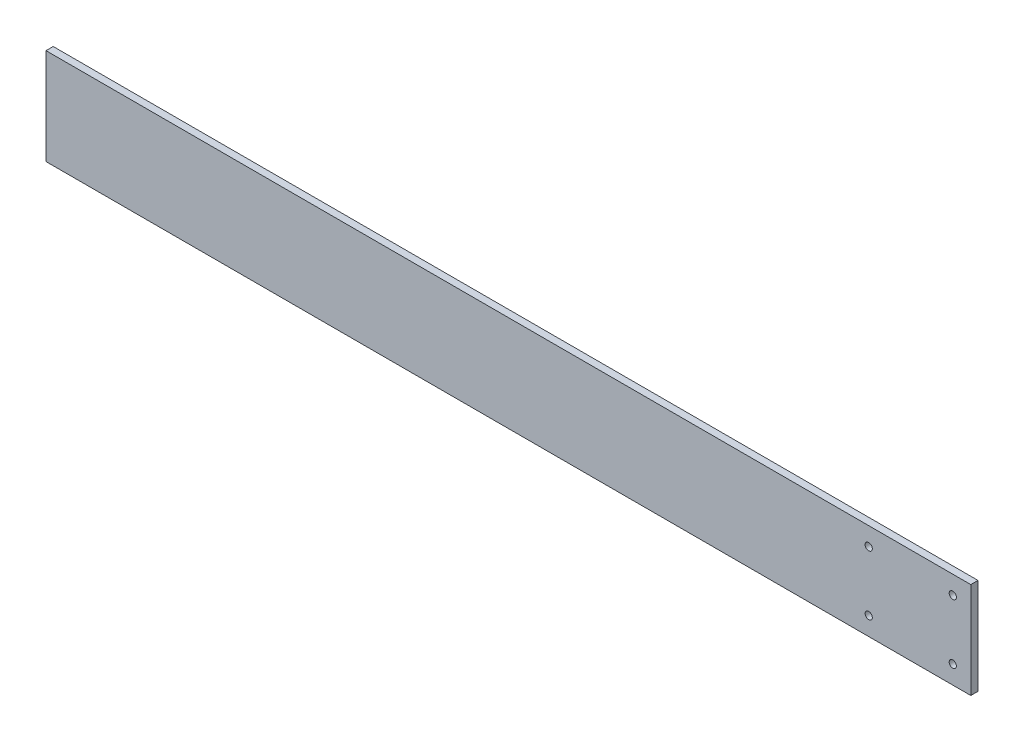
SolidWorks part; units mm, degrees
ref_plane "Front Plane" through (0, 0, 0) normal (0, 0, 1) x (1, 0, 0)
ref_plane "Top Plane" through (0, 0, 0) normal (0, 1, 0) x (1, 0, 0)
ref_plane "Right Plane" through (0, 0, 0) normal (1, 0, 0) x (0, 0, -1)
sketch "Sketch1" plane through (0, 0, 0) normal (0, 0, 1) x (1, 0, 0)
  line L1 (-192.5, -20) -> (192.5, -20)
  line L2 (-192.5, -20) -> (-192.5, 20)
  line L3 (-192.5, 20) -> (192.5, 20)
  line L4 (192.5, -20) -> (192.5, 20)
  line L5 (-192.5, -20) -> (192.5, 20) construction
  line L6 (-192.5, 20) -> (192.5, -20) construction
  point P0 (0, 0)
extrude "Boss-Extrude1" add sketch "Sketch1" along normal blind 3
sketch "Sketch2" plane through (0, 0, 3) normal (0, 0, 1) x (1, 0, 0)
  line L0 (-211.7832, 0) -> (246.0826, 0) construction
  line L1 (0, 63.336) -> (0, -71.7781) construction
  line L8 (167.5, 30.2938) -> (167.5, -33.4197) construction
  line L9 (185, 24.1491) -> (185, -24.1491) construction
  circle A0 centre (185, 12.4206) radius 1.5
  circle A1 centre (185, -12.4206) radius 1.5
  circle A2 centre (150, -12.4206) radius 1.5
  circle A3 centre (150, 12.4206) radius 1.5
  point P11 (0, 0)
  point P16 (0, 0)
  point P22 (185, 0)
extrude "Cut-Extrude2" cut sketch "Sketch2" against normal through all both and the other way through all
